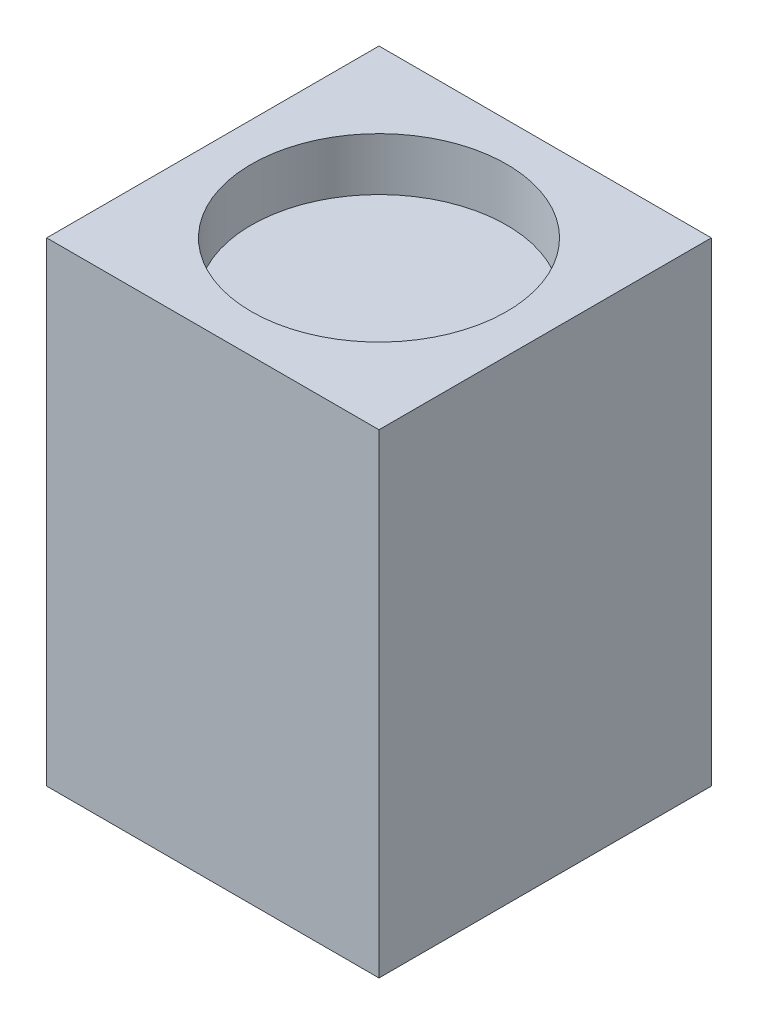
SolidWorks part; units mm, degrees
ref_plane "Front Plane" through (0, 0, 0) normal (0, 0, 1) x (1, 0, 0)
ref_plane "Top Plane" through (0, 0, 0) normal (0, 1, 0) x (1, 0, 0)
ref_plane "Right Plane" through (0, 0, 0) normal (1, 0, 0) x (0, 0, -1)
sketch "Sketch1" plane through (0, 0, 0) normal (0, 1, 0) x (1, 0, 0)
  line L1 (0, -58.2549) -> (0, 58.2549) construction
  line L5 (-58.2549, 0) -> (58.2549, 0) construction
  line L6 (0, 80) -> (-80, 80)
  line L7 (-80, 80) -> (-80, 0)
  line L8 (-80, 0) -> (-80, -80)
  line L9 (-80, -80) -> (0, -80)
  line L10 (80, 0) -> (80, -80)
  line L11 (80, -80) -> (0, -80)
  line L12 (80, 0) -> (80, 80)
  line L13 (80, 80) -> (0, 80)
  circle A0 centre (0, 0) radius 72.136
  point P16 (-80, 0)
  point P17 (0, 80)
  point P18 (80, 0)
  point P19 (0, -80)
extrude "Boss-Extrude1" add sketch "Sketch1" along normal blind 228.6 contours L8 L9 L11 L10 L12 L13 L6 L7
sketch "Sketch3" plane through (0, 228.6, 0) normal (0, 1, 0) x (1, 0, 0)
  circle A0 centre (0, 0) radius 61.468
  dimension "D1" = 122.936
extrude "Cut-Extrude1" cut sketch "Sketch3" against normal blind 25.4 contours A0
